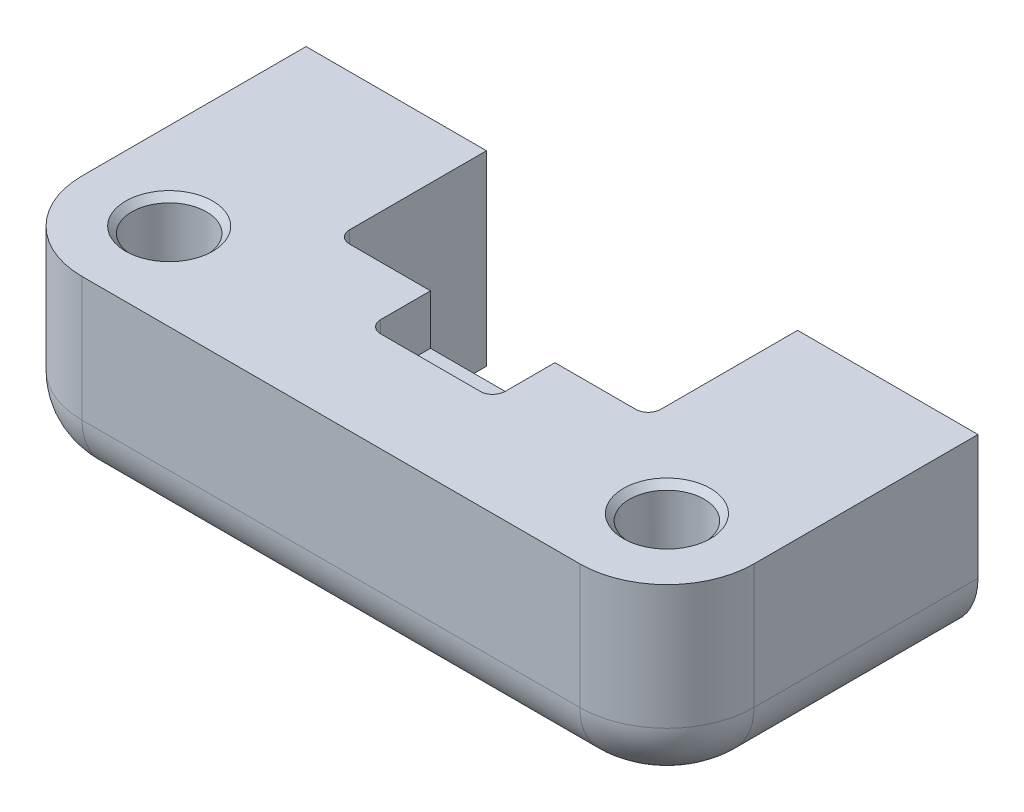
SolidWorks part; units mm, degrees
material "ABS"
ref_plane "前视基准面" through (0, 0, 0) normal (0, 0, 1) x (1, 0, 0)
ref_plane "上视基准面" through (0, 0, 0) normal (0, 1, 0) x (1, 0, 0)
ref_plane "右视基准面" through (0, 0, 0) normal (1, 0, 0) x (0, 0, -1)
other "Configuration Table"
sketch "草图1" plane through (0, 0, 0) normal (0, 0, 1) x (1, 0, 0)
  line L1 (-27, -7.5) -> (27, -7.5)
  line L2 (-27, -7.5) -> (-27, 7.5)
  line L3 (-27, 7.5) -> (27, 7.5)
  line L4 (27, -7.5) -> (27, 7.5)
  line L5 (-27, -7.5) -> (27, 7.5) construction
  line L6 (-27, 7.5) -> (27, -7.5) construction
  point P0 (0, 0)
  dimension "D1" = 54
  dimension "D2" = 15
extrude "凸台-拉伸1" add sketch "草图1" along normal blind 25
sketch "草图2" plane through (0, 7.5, 0) normal (0, -1, 0) x (1, 0, 0)
  line L0 (0, -975) -> (0, 49025) construction
  line L1 (-27, 25) -> (27, 25) construction
  line L2 (-27, 0) -> (27, 0) construction
  circle A0 centre (-20, 18) radius 3
  circle A1 centre (20, 18) radius 3
  point P5 (0, 25)
  dimension "D1" = 6
  dimension "D2" = 40
  dimension "D3" = 18
extrude "切除-拉伸4" cut sketch "草图2" along normal blind 10
sketch "草图3" plane through (0, 0, 0) normal (0, 0, -1) x (-1, 0, 0)
  line L0 (0, -992.5) -> (0, 49007.5) construction
  line L1 (-27, 7.5) -> (27, 7.5) construction
  line L2 (27, -7.5) -> (-27, -7.5) construction
  circle A0 centre (-20, -2.5) radius 2
  circle A1 centre (20, -2.5) radius 2
  point P5 (0, 7.5)
  dimension "D1" = 4
  dimension "D2" = 40
  dimension "D3" = 5
extrude "切除-拉伸5" cut sketch "草图3" against normal blind 9
fillet "圆角1" radius 7 2 edges at (27, 0, 25) (-27, 0, 25)
fillet "圆角2" radius 5 5 edges at (27, -7.5, 9) (24.9497, -7.5, 22.9497) (0, -7.5, 25) (-24.9497, -7.5, 22.9497) (-27, -7.5, 9)
chamfer "倒角1" distance 0.5 angle 45 2 edges at (-20, 7.5, 15) (20, 7.5, 21)
sketch "草图4" plane through (0, 7.5, 0) normal (0, 1, 0) x (1, 0, 0)
  line L0 (0, -1000) -> (0, 49000) construction
  line L1 (27, 0) -> (-27, 0) construction
  line L7 (-11.5, -12) -> (11.5, -12)
  line L8 (-12.5, -11) -> (-12.5, 3)
  line L9 (-11.5, 4) -> (11.5, 4)
  line L10 (12.5, -11) -> (12.5, 3)
  line L11 (-12.5, -12) -> (12.5, 4) construction
  line L12 (-12.5, 4) -> (12.5, -12) construction
  arc A0 (11.5, 4) -> (12.5, 3) centre (11.5, 3) cw
  arc A1 (11.5, -12) -> (12.5, -11) centre (11.5, -11) ccw
  arc A2 (-11.5, -12) -> (-12.5, -11) centre (-11.5, -11) cw
  arc A3 (-12.5, 3) -> (-11.5, 4) centre (-11.5, 3) cw
  point P1 (0, -4)
  point P5 (0, 0)
  dimension "D4" = 1
  dimension "D1" = 25
  dimension "D2" = 4
  dimension "D3" = 12
extrude "切除-拉伸11" cut sketch "草图4" against normal through all both and the other way through all
sketch "草图5" plane through (0, 7.5, 0) normal (0, 1, 0) x (1, 0, 0)
  line L0 (0, -12) -> (0, -25) construction
  line L1 (-11.5, -12) -> (11.5, -12) construction
  line L2 (20, -25) -> (-20, -25) construction
  line L4 (-4, -17) -> (4, -17)
  line L5 (-5, -16) -> (-5, -12)
  line L6 (-5, -12) -> (5, -12)
  line L7 (5, -16) -> (5, -12)
  line L8 (-5, -17) -> (5, -12) construction
  line L9 (-5, -12) -> (5, -17) construction
  arc A0 (4, -17) -> (5, -16) centre (4, -16) ccw
  arc A1 (-4, -17) -> (-5, -16) centre (-4, -16) cw
  point P7 (0, -14.5)
  dimension "D3" = 1
  dimension "D1" = 10
  dimension "D2" = 5
extrude "切除-拉伸12" cut sketch "草图5" against normal blind 4
